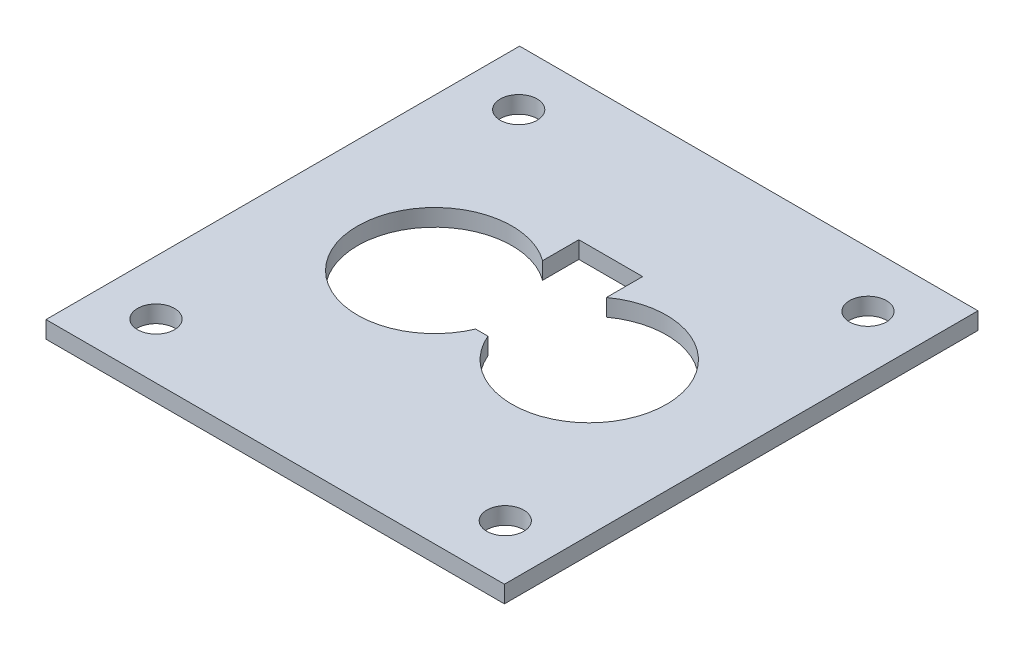
SolidWorks part; units mm, degrees
ref_plane "Front Plane" through (0, 0, 0) normal (0, 0, 1) x (1, 0, 0)
ref_plane "Top Plane" through (0, 0, 0) normal (0, 1, 0) x (1, 0, 0)
ref_plane "Right Plane" through (0, 0, 0) normal (1, 0, 0) x (0, 0, -1)
sketch "Sketch1" plane through (0, 0, 0) normal (0, 1, 0) x (1, 0, 0)
  line L1 (-34.1243, -35.2524) -> (34.1243, -35.2524)
  line L2 (-34.1243, -35.2524) -> (-34.1243, 35.2524)
  line L3 (-34.1243, 35.2524) -> (34.1243, 35.2524)
  line L4 (34.1243, -35.2524) -> (34.1243, 35.2524)
  line L5 (-34.1243, -35.2524) -> (34.1243, 35.2524) construction
  line L6 (-34.1243, 35.2524) -> (34.1243, -35.2524) construction
  point P0 (0, 0)
extrude "Boss-Extrude1" add sketch "Sketch1" along normal blind 2.54
sketch "Sketch2" plane through (0, 2.54, 0) normal (0, 1, 0) x (1, 0, 0)
  line L1 (-26, -27) -> (26, -27)
  line L2 (-26, -27) -> (-26, 27)
  line L3 (-26, 27) -> (26, 27)
  line L4 (26, -27) -> (26, 27)
  line L5 (-26, -27) -> (-11.0662, -11.4918) construction
  line L6 (-26, 27) -> (-11.0662, 11.4918) construction
  line L7 (-4.75, 14.7) -> (4.75, 14.7)
  line L9 (4.3333, -4.5) -> (26, -27) construction
  line L10 (-4.75, 14.7) -> (4.75, 14.7)
  line L11 (-4.75, 14.7) -> (-4.75, 9.3106)
  line L13 (4.75, 14.7) -> (4.75, 9.3106)
  line L16 (11.0662, 11.4918) -> (26, 27) construction
  line L17 (4.3333, -4.5) -> (4.75, -4.5)
  line L18 (4.3333, -4.5) -> (4.75, -4.5)
  line L19 (-0.917, -4.5) -> (0.917, -4.5)
  line L20 (-0.917, -4.5) -> (0.917, -4.5)
  arc A0 (-4.75, 9.3106) -> (-0.917, -4.5) centre (-11.5, 0) ccw
  arc A1 (0.917, -4.5) -> (4.75, 9.3106) centre (11.5, 0) ccw
  point P0 (0, 0)
  point P9 (0, 0)
  point P14 (0, 14.7)
  point P18 (0, -4.5)
  dimension "D4" = 23
  dimension "D5" = 23
  dimension "D1" = 52
  dimension "D2" = 54
  dimension "D3" = 23
  dimension "D6" = 9.5
  dimension "D7" = 14.7
hole_wizard "M5 Clearance Hole1" positions "Sketch3" profile "Sketch4" hole size "M5" standard "ANSI Metric" end condition up to next
sketch "Sketch3" plane through (0, 2.54, 0) normal (0, 1, 0) x (1, 0, 0)
  point P0 (26, 27)
  point P3 (-26, 27)
  point P6 (-26, -27)
  point P9 (26, -27)
sketch "Sketch4" plane through (26, 2.54, -27) normal (1, 0, 0) x (0, 0, 1)
  line L0 (0, 0) -> (0, 2.54)
  line L1 (0, 2.54) -> (2.75, 2.54)
  line L2 (2.75, 2.54) -> (2.75, 0)
  line L5 (2.75, 0) -> (0, 0)
  line L11 (0, -6.35) -> (0, 107.95) construction
  dimension "Thru Hole Dia." = 5.5
  dimension "Thru Hole Depth" = 2.54
extrude "Cut-Extrude1" cut sketch "Sketch2" against normal through all
